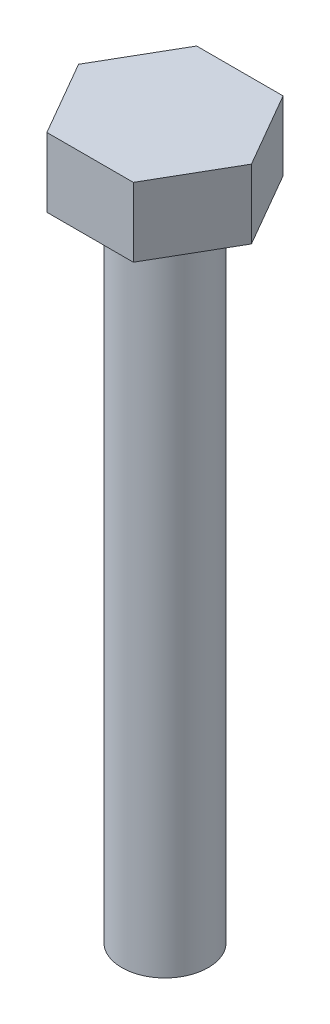
SolidWorks part; units mm, degrees
material "Alliage 1060"
ref_plane "Plan de face" through (0, 0, 0) normal (0, 0, 1) x (1, 0, 0)
ref_plane "Plan de dessus" through (0, 0, 0) normal (0, 1, 0) x (1, 0, 0)
ref_plane "Plan de droite" through (0, 0, 0) normal (1, 0, 0) x (0, 0, -1)
sketch "Esquisse1" plane through (0, 0, 0) normal (0, 1, 0) x (1, 0, 0)
  circle A0 centre (0, 0) radius 5
  dimension "D1" = 10
extrude "Boss.-Extru.1" add sketch "Esquisse1" along normal blind 75
sketch "Esquisse2" plane through (0, 75, 0) normal (0, 1, 0) x (1, 0, 0)
  line L0 (-5, 8.6603) -> (5, 8.6603)
  line L1 (5, 8.6603) -> (10, 0)
  line L2 (10, 0) -> (5, -8.6603)
  line L3 (5, -8.6603) -> (-5, -8.6603)
  line L4 (-5, -8.6603) -> (-10, 0)
  line L5 (-10, 0) -> (-5, 8.6603)
  point P7 (0, 8.6603)
  dimension "D1" = 120
  dimension "D2" = 120
  dimension "D3" = 10
extrude "Boss.-Extru.2" add sketch "Esquisse2" along normal blind 8
sketch "Esquisse4" plane through (0, 0, 0) normal (0, -1, 0) x (1, 0, 0)
  circle A0 centre (0, 0) radius 5
  dimension "D1" = 10
